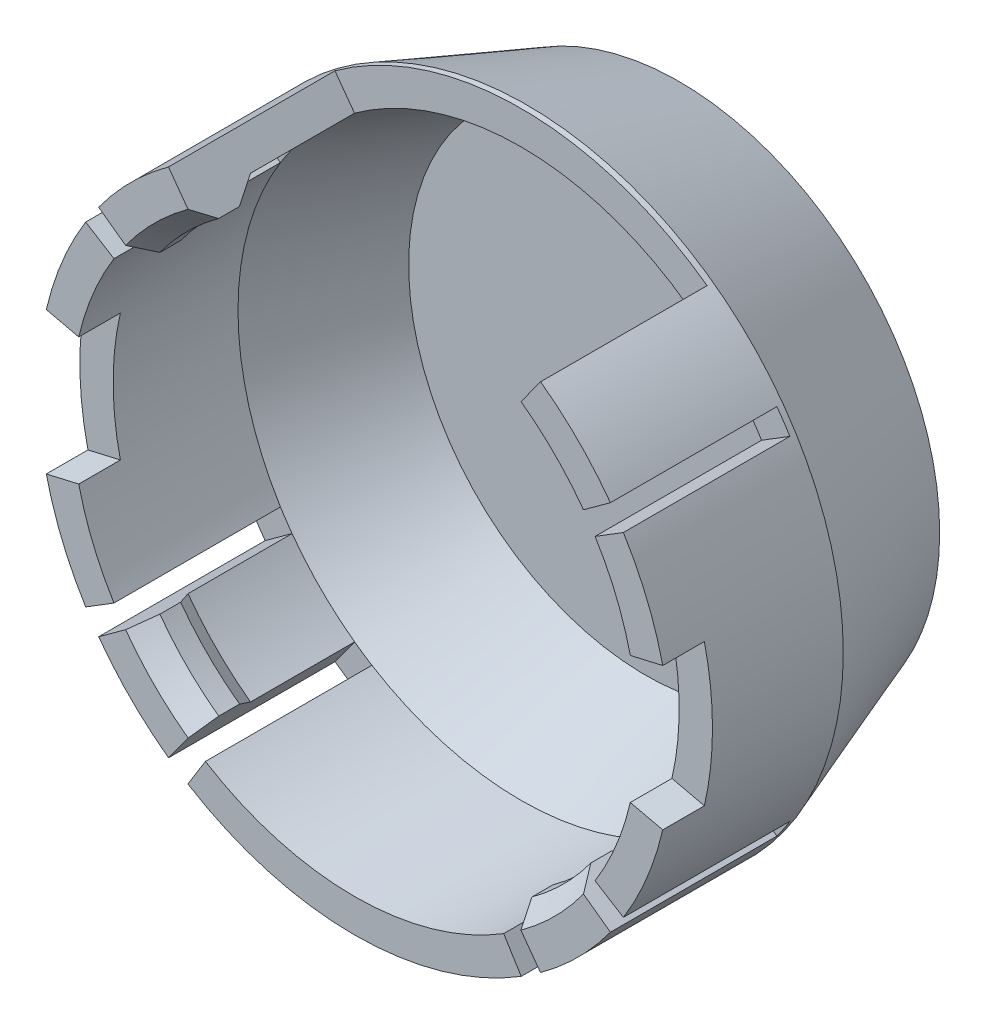
SolidWorks part; units mm, degrees
ref_plane "Front Plane" through (0, 0, 0) normal (0, 0, 1) x (1, 0, 0)
ref_plane "Top Plane" through (0, 0, 0) normal (0, 1, 0) x (1, 0, 0)
ref_plane "Right Plane" through (0, 0, 0) normal (1, 0, 0) x (0, 0, -1)
sketch "Sketch1" plane through (0, 0, 0) normal (1, 0, 0) x (0, 0, -1)
  line L0 (0, 15.2) -> (8.2841, 15.2)
  line L1 (8.2841, 15.2) -> (15.6, 12.5175)
  line L2 (15.6, 12.5175) -> (15.6, 0)
  line L3 (14, 0) -> (15.6, 0)
  line L4 (2, 12.8) -> (1, 12.8)
  line L5 (2, 12.8) -> (3, 13.6)
  line L6 (14, 0) -> (14, 11.4)
  line L7 (14, 11.4) -> (8, 13.6)
  line L8 (8, 13.6) -> (3, 13.6)
  line L9 (0, 13.6) -> (0, 15.2)
  line L10 (1, 12.8) -> (0, 13.6)
  dimension "D1" = 11.4
  dimension "D2" = 13.6
  dimension "D3" = 14
  dimension "D4" = 1
  dimension "D5" = 1.6
  dimension "D6" = 1.6
  dimension "D7" = 8
  dimension "D8" = 3
  dimension "D9" = 0.8
revolve "Revolve1" add sketch "Sketch1" angle 360 about L3
sketch "Sketch2" plane through (0, 0, 0) normal (0, 0, 1) x (1, 0, 0)
  line L0 (-7.5294, 10.3512) -> (0, 0) construction
  line L1 (-11.0564, 15.2) -> (11.0564, 15.2)
  line L2 (-11.0564, 15.2) -> (-7.5294, 10.3512)
  line L3 (-7.5294, 10.3512) -> (7.5294, 10.3512)
  line L4 (11.0564, 15.2) -> (7.5294, 10.3512)
  line L5 (0, 0) -> (7.5294, 10.3512) construction
  line L6 (-8, 10.9982) -> (8, 10.9982) construction
  circle A0 centre (0, 0) radius 12.8 construction
  circle A1 centre (0, 0) radius 15.2 construction
  circle A3 centre (0, 0) radius 13.6 construction
  dimension "D1" = 16
extrude "Cut-Extrude1" cut sketch "Sketch2" against normal blind 8
sketch "Sketch3" plane through (0, 0, 0) normal (0, 0, 1) x (1, 0, 0)
  line L0 (-8.9366, 12.2954) -> (-7.5256, 10.354)
  line L1 (-7.5256, 10.354) -> (-10.354, 7.5256)
  line L2 (-10.354, 7.5256) -> (-12.2954, 8.9366)
  line L3 (-8.009, 12.9188) -> (-7.166, 11.5589)
  line L4 (-12.9192, 8.0084) -> (-11.5593, 7.1654)
  line L5 (-11.5593, 7.1654) -> (-10.9714, 7.9743) construction
  line L6 (0, 0) -> (0, 13.6)
  line L7 (-7.166, 11.5589) -> (-7.9959, 11.0011) construction
  line L8 (-13.6, 0) -> (0, 0)
  line L11 (0, 0) -> (-12.6174, 12.6174) construction
  line L12 (-11.5593, 7.1654) -> (0, 0) construction
  line L14 (-10.354, 7.5256) -> (0, 0) construction
  line L15 (-7.5256, 10.354) -> (0, 0) construction
  line L17 (-7.166, 11.5589) -> (0.0166, -0.0268) construction
  arc A0 (-8.9366, 12.2954) -> (-8.009, 12.9188) centre (0, 0) cw
  arc A1 (-7.166, 11.5589) -> (0, 13.6) centre (0, 0) cw
  arc A2 (-12.2954, 8.9366) -> (-12.9192, 8.0084) centre (0, 0) ccw
  arc A3 (-11.5593, 7.1654) -> (-13.6, 0) centre (0, 0) ccw
  arc A4 (-8, 10.9982) -> (8, 10.9982) centre (0, 0) ccw construction
  arc A6 (-8.9412, 12.2921) -> (8.9412, 12.2921) centre (0, 0) ccw construction
  arc A7 (-8, -10.9982) -> (8, -10.9982) centre (0, 0) ccw construction
  arc A8 (-7.5294, 10.3512) -> (7.5294, 10.3512) centre (0, 0) ccw construction
  arc A9 (8.9412, 12.2921) -> (-8.9412, 12.2921) centre (0, 0) ccw construction
  circle A10 centre (0, 0) radius 13.6 construction
  dimension "D1" = 45
  dimension "D2" = 2
  dimension "D3" = 4
  dimension "D4" = 1
extrude "Cut-Extrude2" cut sketch "Sketch3" against normal up to surface (8 mm away)
pattern_circular "CirPattern1" count 4 over 360 about axis through (0, 0, 0) along (0, 0, 1) of "Cut-Extrude2"
sketch "Sketch4" plane through (0, 0, 0) normal (0, 0, 1) x (1, 0, 0)
  line L0 (-14.2, 2.7402) -> (-14.2, -2.3125) construction
  line L1 (14.2, 2.2109) -> (14.2, -2.3125) construction
  line L2 (-11.5, 0) -> (11.5, 0) construction
  line L3 (0, 0) -> (-14.8104, 3.4193)
  line L4 (-14.8104, -3.4193) -> (0, 0)
  line L5 (14.8104, 3.4193) -> (0, 0)
  line L6 (0, 0) -> (14.8104, -3.4193)
  circle A0 centre (-11.5, 0) radius 2.7 construction
  circle A1 centre (11.5, 0) radius 2.7 construction
  arc A2 (-12.9192, 8.0084) -> (-12.9188, -8.009) centre (0, 0) ccw construction
  arc A3 (-14.8104, 3.4193) -> (-14.8104, -3.4193) centre (0, 0) ccw
  arc A4 (14.8104, -3.4193) -> (14.8104, 3.4193) centre (0, 0) ccw
  arc A5 (12.9192, -8.0084) -> (12.9188, 8.009) centre (0, 0) ccw construction
  dimension "D1" = 5.4
  dimension "D4" = 13
  dimension "D2" = 28.4
  dimension "D3" = 14.2
  dimension "D5" = 13
extrude "Cut-Extrude3" cut sketch "Sketch4" against normal blind 2 contours L3 A3 L4 | L6 A4 L5
